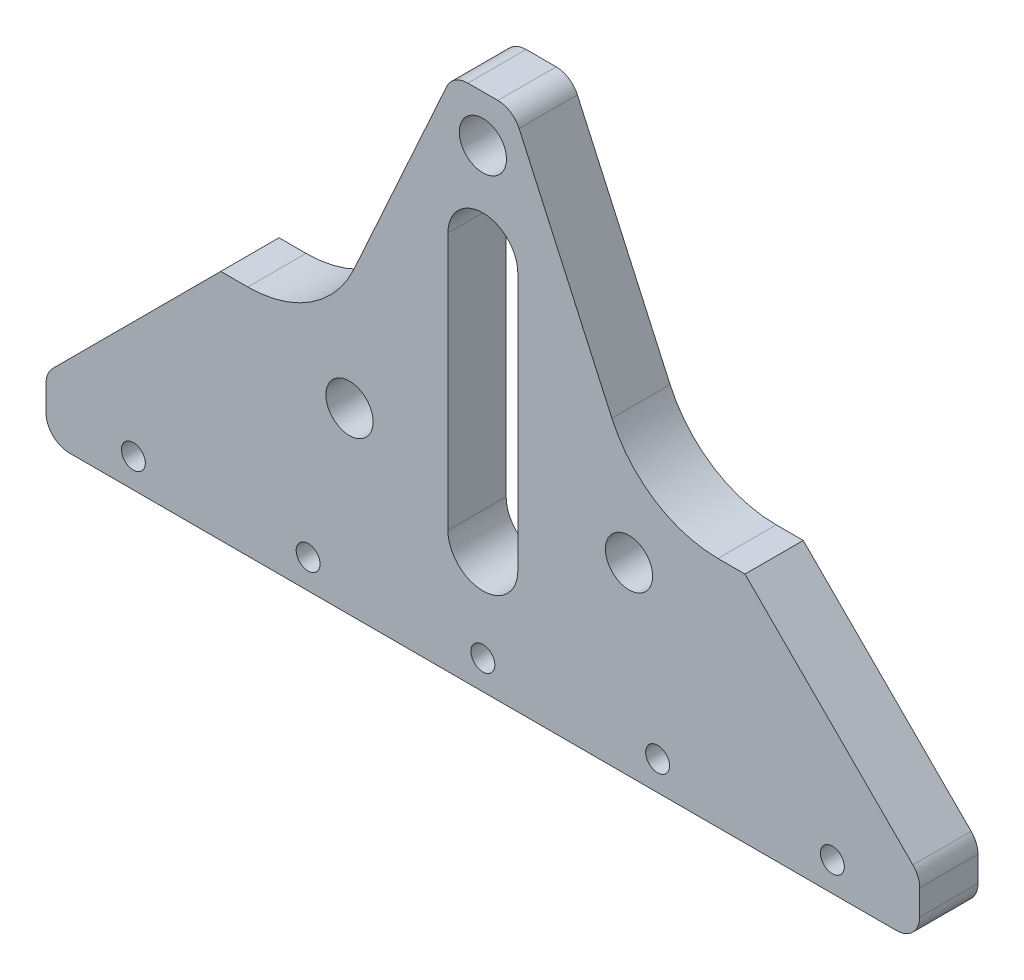
SolidWorks part; units mm, degrees
material "Thornel Mat VMA"
ref_plane "前视基准面" through (0, 0, 0) normal (0, 0, 1) x (1, 0, 0)
ref_plane "上视基准面" through (0, 0, 0) normal (0, 1, 0) x (1, 0, 0)
ref_plane "右视基准面" through (0, 0, 0) normal (1, 0, 0) x (0, 0, -1)
other "Configuration Table"
sketch "草图1" plane through (0, 0, 0) normal (0, 0, 1) x (1, 0, 0)
  line L1 (-37.5, -28) -> (37.5, -28)
  line L2 (-37.5, -28) -> (-37.5, 28)
  line L3 (-37.5, 28) -> (37.5, 28)
  line L4 (37.5, -28) -> (37.5, 28)
  line L5 (-37.5, -28) -> (37.5, 28) construction
  line L6 (-37.5, 28) -> (37.5, -28) construction
  point P0 (0, 0)
  dimension "D1" = 75
  dimension "D2" = 56
extrude "凸台-拉伸1" add sketch "草图1" along normal blind 5
sketch "草图2" plane through (0, 0, 0) normal (0, 0, -1) x (-1, 0, 0)
  circle A0 centre (11.4497, -12.6534) radius 2.025 construction
  circle A1 centre (0, 12.6034) radius 2.025 construction
  circle A2 centre (-12.5446, -12.1278) radius 2.025 construction
  circle A3 centre (11.4497, -12.6534) radius 2.025
  circle A4 centre (0, 12.6034) radius 2.025
  circle A5 centre (-12.5446, -12.1278) radius 2.025
extrude "切除-拉伸1" cut sketch "草图2" against normal blind 5
sketch "草图3" plane through (0, 0, 0) normal (0, 0, -1) x (-1, 0, 0)
  line L0 (0, 12.6034) -> (11.4497, -12.6534) construction
  line L1 (0, 12.6034) -> (-12.5446, -12.1278) construction
  line L2 (2.5785, 16.6034) -> (13.732, -8)
  line L4 (-37.5, -28) -> (-37.5, 28) construction
  line L5 (-37.5, -8) -> (-37.5, 28)
  line L6 (-37.5, 28) -> (37.5, 28)
  line L7 (-37.5, 28) -> (37.5, 28) construction
  line L8 (0, 28) -> (0, 16.6034) construction
  line L9 (0, 16.6034) -> (2.5785, 16.6034)
  line L10 (37.5, -8) -> (37.5, 28)
  line L11 (-2.5785, 16.6034) -> (-13.732, -8)
  line L13 (0, 16.6034) -> (-2.5785, 16.6034)
  line L14 (37.5, 28) -> (37.5, -28) construction
  line L15 (13.732, -8) -> (37.5, -8)
  line L16 (-13.732, -8) -> (-37.5, -8)
  circle A0 centre (11.4497, -12.6534) radius 2.025 construction
  point P22 (4.9483, -8)
  point P23 (-4.9218, 16.6034)
  point P24 (37.5, -8)
  dimension "D1" = 4
  dimension "D2" = 4
  dimension "D3" = 36
  dimension "D4" = 4.6534
extrude "切除-拉伸2" cut sketch "草图3" against normal blind 5
fillet "圆角1" radius 10 2 edges at (-13.732, -8, 2.5) (13.732, -8, 2.5)
sketch "草图4" plane through (0, 0, 0) normal (0, 0, -1) x (-1, 0, 0)
  circle A0 centre (30, -25.5) radius 1.2 construction
  circle A1 centre (30, -25.5) radius 1.2 construction
  circle A2 centre (30, -25.5) radius 1.025
  circle A3 centre (15, -25.5) radius 1.025
  circle A4 centre (0, -25.5) radius 1.025
  circle A5 centre (-15, -25.5) radius 1.025
  circle A6 centre (-30, -25.5) radius 1.025
  dimension "D1" = 2.05
  dimension "D3" = 15
  dimension "D2" = 5
extrude "切除-拉伸3" cut sketch "草图4" against normal blind 21.4
sketch "草图5" plane through (0, 0, 0) normal (0, 0, -1) x (-1, 0, 0)
  line L0 (-37.5, -23) -> (37.5, -23) construction
  line L1 (-37.5, -28) -> (-37.5, -8) construction
  line L2 (37.5, -8) -> (37.5, -28) construction
  line L3 (37.5, -28) -> (-37.5, -28) construction
  line L4 (-37.5, -23) -> (-22.5, -8)
  line L6 (22.5, -8) -> (37.5, -23)
  line L8 (-22.5, -8) -> (-37.5, -8)
  line L9 (-37.5, -8) -> (-37.5, -23)
  line L10 (22.5, -8) -> (37.5, -8)
  line L11 (37.5, -8) -> (37.5, -23)
  line L12 (20.1782, -8) -> (37.5, -8) construction
  line L13 (-37.5, -8) -> (-20.1782, -8) construction
  point P10 (22.4002, -8)
  point P13 (-22.3807, -8)
  dimension "D1" = 5
  dimension "D2" = 45
  dimension "D3" = 45
extrude "切除-拉伸4" cut sketch "草图5" against normal blind 81.4
sketch "草图6" plane through (0, 0, 0) normal (0, 0, -1) x (-1, 0, 0)
  line L0 (0, -17.5) -> (0, 4.6034) construction
  line L1 (-3, -17.5) -> (-3, 4.6034)
  line L2 (3, -17.5) -> (3, 4.6034)
  arc A0 (-3, -17.5) -> (3, -17.5) centre (0, -17.5) ccw
  arc A1 (3, 4.6034) -> (-3, 4.6034) centre (0, 4.6034) ccw
  circle A2 centre (0, 12.6034) radius 2.025 construction
  circle A3 centre (0, -25.5) radius 1.025 construction
  point P3 (0, -6.4483)
  point P8 (0, -17.0996)
  dimension "D1" = 3
  dimension "D2" = 8
  dimension "D3" = 8
extrude "切除-拉伸5" cut sketch "草图6" against normal blind 81.4
fillet "圆角2" radius 2 4 edges at (37.5, -23, 2.5) (37.5, -28, 2.5) (-37.5, -28, 2.5) (-37.5, -23, 2.5)
fillet "圆角3" radius 2 2 edges at (2.5785, 16.6034, 2.5) (-2.5785, 16.6034, 2.5)
